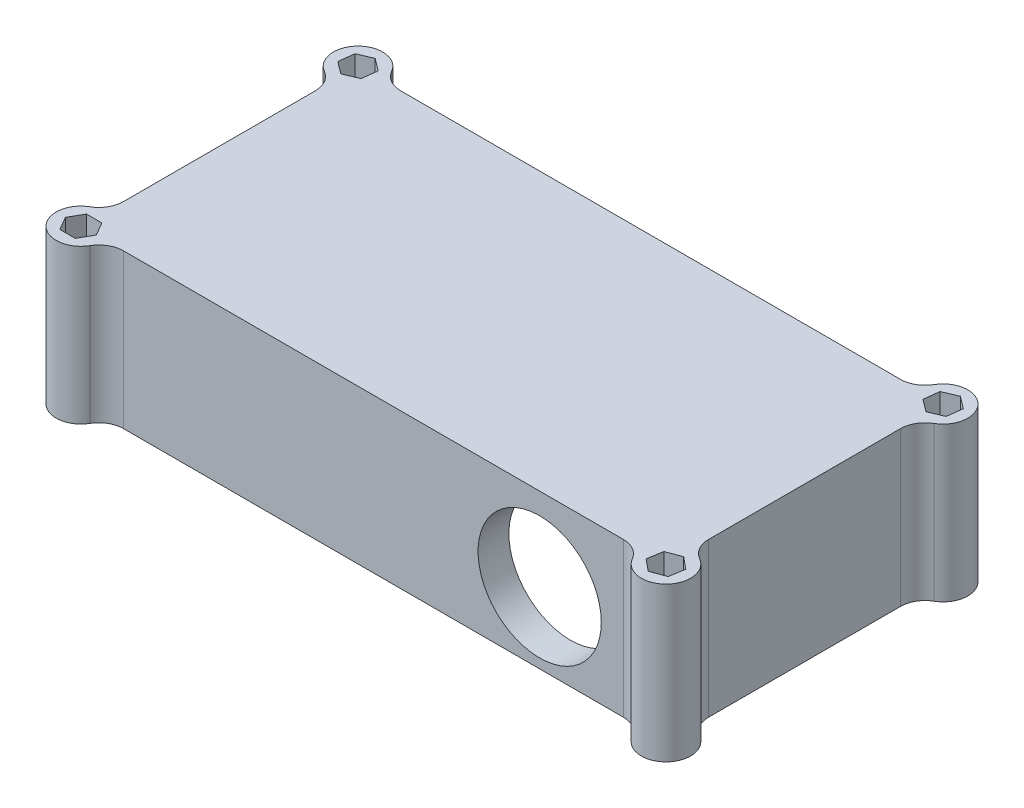
SolidWorks part; units mm, degrees
ref_plane "Front Plane" through (0, 0, 0) normal (0, 0, 1) x (1, 0, 0)
ref_plane "Top Plane" through (0, 0, 0) normal (0, 1, 0) x (1, 0, 0)
ref_plane "Right Plane" through (0, 0, 0) normal (1, 0, 0) x (0, 0, -1)
sketch "Sketch2" plane through (0, 0, 0) normal (0, 1, 0) x (1, 0, 0)
  line L0 (0, 0) -> (0, 33.7204) construction
  line L1 (-47.5, 22.5) -> (47.5, 22.5)
  line L2 (-47.5, 22.5) -> (-47.5, -22.5)
  line L3 (-47.5, -22.5) -> (47.5, -22.5)
  line L4 (47.5, 22.5) -> (47.5, -22.5)
  line L5 (-47.5, 22.5) -> (47.5, -22.5) construction
  line L6 (-47.5, -22.5) -> (47.5, 22.5) construction
  line L7 (-37.5, 12.5) -> (37.5, 12.5)
  line L8 (-37.5, 12.5) -> (-37.5, -12.5)
  line L9 (-37.5, -12.5) -> (37.5, -12.5)
  line L10 (37.5, 12.5) -> (37.5, -12.5)
  line L11 (-37.5, 12.5) -> (37.5, -12.5) construction
  line L12 (-37.5, -12.5) -> (37.5, 12.5) construction
  line L13 (0, 0) -> (-56.7787, 0) construction
  circle A0 centre (-47.5, 22.5) radius 4
  circle A1 centre (-47.5, 22.5) radius 1.5
  circle A2 centre (-47.5, -22.5) radius 1.5
  circle A3 centre (-47.5, -22.5) radius 4
  circle A4 centre (47.5, 22.5) radius 4
  circle A5 centre (47.5, -22.5) radius 1.5
  circle A6 centre (47.5, -22.5) radius 4
  circle A7 centre (47.5, 22.5) radius 1.5
  point P0 (0, 0)
  point P6 (0, 0)
  dimension "D5" = 3
  dimension "D6" = 8
  dimension "D1" = 75
  dimension "D2" = 25
  dimension "D3" = 10
  dimension "D4" = 10
extrude "Boss-Extrude1" add sketch "Sketch2" along normal blind 25 contours L4 A7 L1 A4 | L1 A7 L4 A4 | L3 A6 L4 A5 | L4 A6 L3 A5 | A3 L2 A2 L3 | A3 L3 A2 L2 | A1 L2 A0 L1 | A1 L1 A0 L2 | A6 L4 A4 L1 A0 L2 A3 L3 L7 L10 L9 L8 | L10 L7 L8 L9
fillet "Fillet3" radius 4 1 edges at (-43.5, 12.5, -22.5)
fillet "Fillet4" radius 4 1 edges at (-47.5, 12.5, -18.5)
fillet "Fillet5" radius 4 1 edges at (47.5, 12.5, -18.5)
fillet "Fillet6" radius 4 1 edges at (43.5, 12.5, -22.5)
fillet "Fillet7" radius 4 1 edges at (47.5, 12.5, 18.5)
fillet "Fillet8" radius 4 1 edges at (43.5, 12.5, 22.5)
fillet "Fillet9" radius 4 1 edges at (-43.5, 12.5, 22.5)
fillet "Fillet10" radius 4 1 edges at (-47.5, 12.5, 18.5)
sketch "Sketch3" plane through (0, 25, 0) normal (0, 1, 0) x (1, 0, 0)
  line L1 (45.159, -23.3774) -> (47.0894, -24.9661)
  line L2 (47.0894, -24.9661) -> (49.4304, -24.0886)
  line L3 (49.4304, -24.0886) -> (49.841, -21.6226)
  line L4 (49.841, -21.6226) -> (47.9106, -20.0339)
  line L5 (47.9106, -20.0339) -> (45.5696, -20.9114)
  line L6 (45.5696, -20.9114) -> (45.159, -23.3774)
  line L7 (45.1987, 21.5234) -> (47.1951, 20.0187)
  line L8 (47.1951, 20.0187) -> (49.4965, 20.9953)
  line L9 (49.4965, 20.9953) -> (49.8013, 23.4766)
  line L10 (49.8013, 23.4766) -> (47.8049, 24.9813)
  line L11 (47.8049, 24.9813) -> (45.5035, 24.0047)
  line L12 (45.5035, 24.0047) -> (45.1987, 21.5234)
  line L13 (-49.8013, 21.5234) -> (-47.8049, 20.0187)
  line L14 (-47.8049, 20.0187) -> (-45.5035, 20.9953)
  line L15 (-45.5035, 20.9953) -> (-45.1987, 23.4766)
  line L16 (-45.1987, 23.4766) -> (-47.1951, 24.9813)
  line L17 (-47.1951, 24.9813) -> (-49.4965, 24.0047)
  line L18 (-49.4965, 24.0047) -> (-49.8013, 21.5234)
  line L19 (-50, -22.5) -> (-48.75, -24.6651)
  line L20 (-48.75, -24.6651) -> (-46.25, -24.6651)
  line L21 (-46.25, -24.6651) -> (-45, -22.5)
  line L22 (-45, -22.5) -> (-46.25, -20.3349)
  line L23 (-46.25, -20.3349) -> (-48.75, -20.3349)
  line L24 (-48.75, -20.3349) -> (-50, -22.5)
  circle A4 centre (47.5, -22.5) radius 2.1651 construction
  circle A5 centre (47.5, 22.5) radius 2.1651 construction
  circle A6 centre (-47.5, 22.5) radius 2.1651 construction
  circle A7 centre (-47.5, -22.5) radius 2.1651 construction
extrude "Cut-Extrude1" cut sketch "Sketch3" against normal blind 10
sketch "Sketch4" plane through (0, 0, 0) normal (0, -1, 0) x (1, 0, 0)
  line L8 (-42.5, 15.5718) -> (-42.5, -15.5718)
  line L9 (-40.5718, -17.5) -> (40.5718, -17.5)
  line L10 (42.5, -15.5718) -> (42.5, 15.5718)
  line L11 (40.5718, 17.5) -> (-40.5718, 17.5)
  line L12 (-42.5, 15.5718) -> (-42.5, -15.5718)
  line L13 (-40.5718, -17.5) -> (40.5718, -17.5)
  line L14 (42.5, -15.5718) -> (42.5, 15.5718)
  line L15 (40.5718, 17.5) -> (-40.5718, 17.5)
  arc A24 (-42.7734, 17.7734) -> (-40.5718, 17.5) centre (-40.5718, 26.5) ccw
  arc A25 (-42.5, 15.5718) -> (-42.7734, 17.7734) centre (-51.5, 15.5718) ccw
  arc A26 (-42.7734, -17.7734) -> (-42.5, -15.5718) centre (-51.5, -15.5718) ccw
  arc A27 (-40.5718, -17.5) -> (-42.7734, -17.7734) centre (-40.5718, -26.5) ccw
  arc A28 (42.7734, -17.7734) -> (40.5718, -17.5) centre (40.5718, -26.5) ccw
  arc A29 (42.5, -15.5718) -> (42.7734, -17.7734) centre (51.5, -15.5718) ccw
  arc A30 (42.7734, 17.7734) -> (42.5, 15.5718) centre (51.5, 15.5718) ccw
  arc A31 (40.5718, 17.5) -> (42.7734, 17.7734) centre (40.5718, 26.5) ccw
  arc A32 (-42.7734, 17.7734) -> (-40.5718, 17.5) centre (-40.5718, 26.5) ccw
  arc A33 (-42.5, 15.5718) -> (-42.7734, 17.7734) centre (-51.5, 15.5718) ccw
  arc A34 (-42.7734, -17.7734) -> (-42.5, -15.5718) centre (-51.5, -15.5718) ccw
  arc A35 (-40.5718, -17.5) -> (-42.7734, -17.7734) centre (-40.5718, -26.5) ccw
  arc A36 (42.7734, -17.7734) -> (40.5718, -17.5) centre (40.5718, -26.5) ccw
  arc A37 (42.5, -15.5718) -> (42.7734, -17.7734) centre (51.5, -15.5718) ccw
  arc A38 (42.7734, 17.7734) -> (42.5, 15.5718) centre (51.5, 15.5718) ccw
  arc A39 (40.5718, 17.5) -> (42.7734, 17.7734) centre (40.5718, 26.5) ccw
  dimension "D1" = 5
extrude "Cut-Extrude2" cut sketch "Sketch4" against normal offset from surface (20 mm away) 5 up to face at (-47.5, 25, 22.5)
sketch "Sketch5" plane through (-47.5, 0, 0) normal (-1, 0, 0) x (0, 0, 1)
  line L1 (9.9014, 7.6231) -> (-9.2263, 7.6231)
  line L2 (9.9014, 7.6231) -> (9.9014, 18.5)
  line L3 (9.9014, 18.5) -> (-9.2263, 18.5)
  line L4 (-9.2263, 7.6231) -> (-9.2263, 18.5)
extrude "Cut-Extrude3" cut sketch "Sketch5" against normal up to surface (5 mm away) up to face at (-42.5, 10, 0)
sketch "Sketch6" plane through (0, 0, 22.5) normal (0, 0, 1) x (1, 0, 0)
  circle A0 centre (26.9928, 11.5323) radius 10
  dimension "D1" = 20
extrude "Cut-Extrude4" cut sketch "Sketch6" against normal up to surface (5 mm away) up to face at (0, 10, 17.5)
